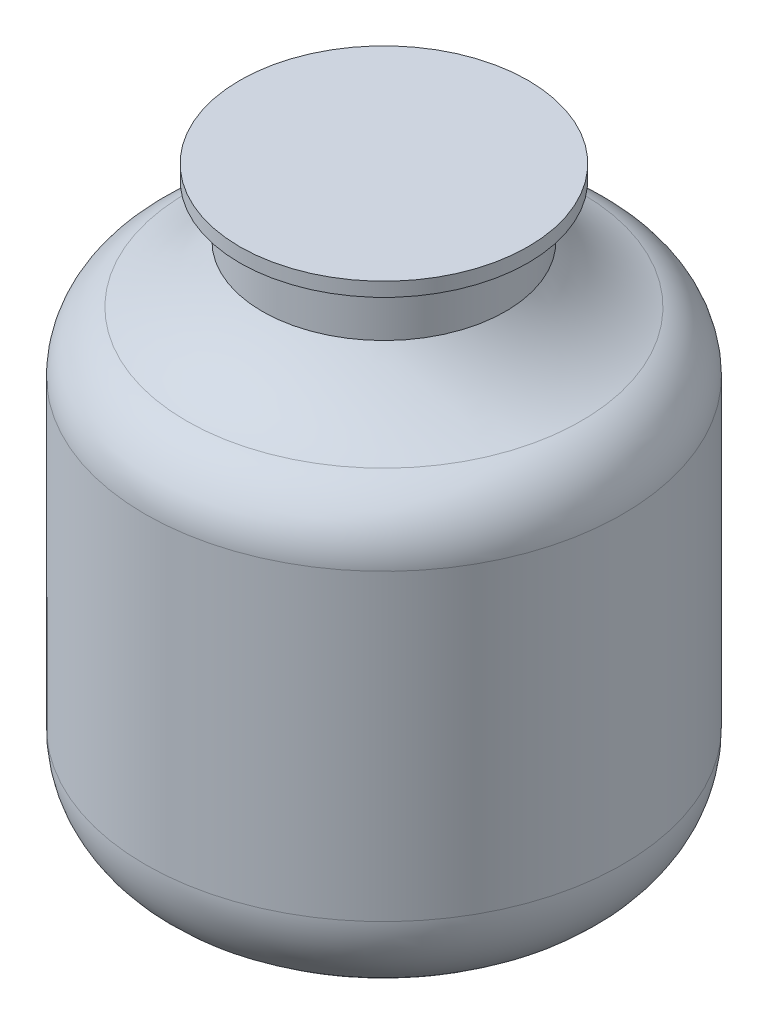
SolidWorks part; units mm, degrees
material "AISI 1020"
ref_plane "Front Plane" through (0, 0, 0) normal (0, 0, 1) x (1, 0, 0)
ref_plane "Top Plane" through (0, 0, 0) normal (0, 1, 0) x (1, 0, 0)
ref_plane "Right Plane" through (0, 0, 0) normal (1, 0, 0) x (0, 0, -1)
sketch "Sketch1" plane through (0, 0, 0) normal (0, 0, 1) x (1, 0, 0)
  line L0 (0, 0) -> (24.3601, 0)
  line L1 (40.3285, 15.9684) -> (40.3285, 67.2302)
  line L2 (20.5561, 87.0228) -> (20.5561, 96.025)
  line L3 (20.5561, 96.025) -> (24.3601, 96.025)
  line L4 (24.3601, 96.025) -> (24.3601, 98.394)
  line L5 (24.3601, 98.394) -> (0, 98.394)
  line L6 (0, 98.394) -> (0, 0)
  arc A0 (24.3601, 0) -> (40.3285, 15.9684) centre (24.3601, 15.9684) ccw
  arc A1 (40.3285, 67.2302) -> (33.3486, 77.3889) centre (29.4459, 67.2302) ccw
  arc A2 (33.3486, 77.3889) -> (20.5561, 87.0228) centre (43.7873, 104.5604) cw
revolve "Revolve1" add sketch "Sketch1" angle 360 about L6
